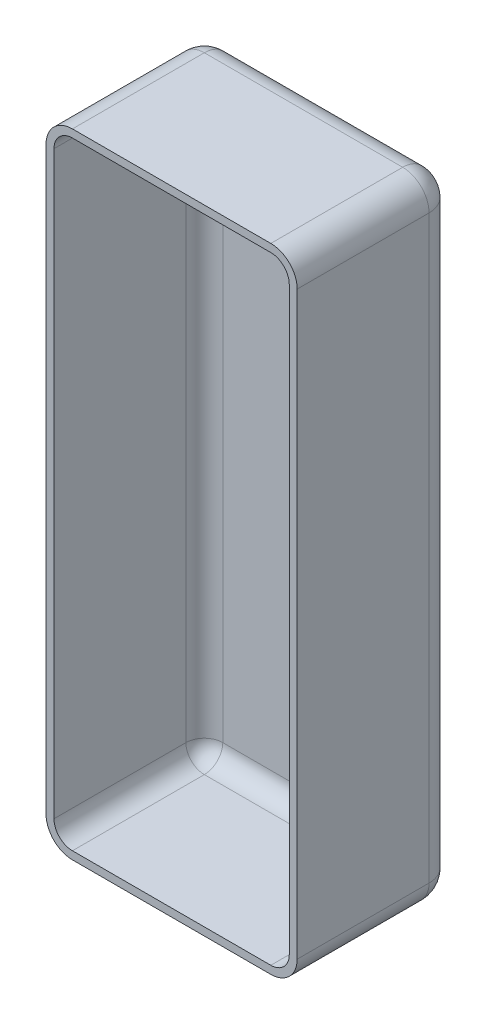
SolidWorks part; units mm, degrees
ref_plane "Alzado" through (0, 0, 0) normal (0, 0, 1) x (1, 0, 0)
ref_plane "Planta" through (0, 0, 0) normal (0, 1, 0) x (1, 0, 0)
ref_plane "Vista lateral" through (0, 0, 0) normal (1, 0, 0) x (0, 0, -1)
sketch "Croquis1" plane through (0, 0, 0) normal (0, 0, 1) x (1, 0, 0)
  line L0 (0, 259.1499) -> (0, -218.0794) construction
  line L1 (-47.6, 120) -> (47.6, 120)
  line L2 (-47.6, 120) -> (-47.6, -120)
  line L3 (-47.6, -120) -> (47.6, -120)
  line L4 (47.6, 120) -> (47.6, -120)
  line L5 (-98.8232, 0) -> (105.8652, 0) construction
  dimension "D1" = 95.2
  dimension "D2" = 240
  dimension "D3" = 120
  dimension "D4" = 47.6
extrude "Saliente-Extruir1" add sketch "Croquis1" along normal blind 60
fillet "Redondeo1" radius 10 8 edges at (0, -120, 0) (0, 120, 0) (47.6, 0, 0) (-47.6, 0, 0) (-47.6, -120, 30) (47.6, -120, 30) (-47.6, 120, 30) (47.6, 120, 30)
shell "Vaciado1" thickness 3
